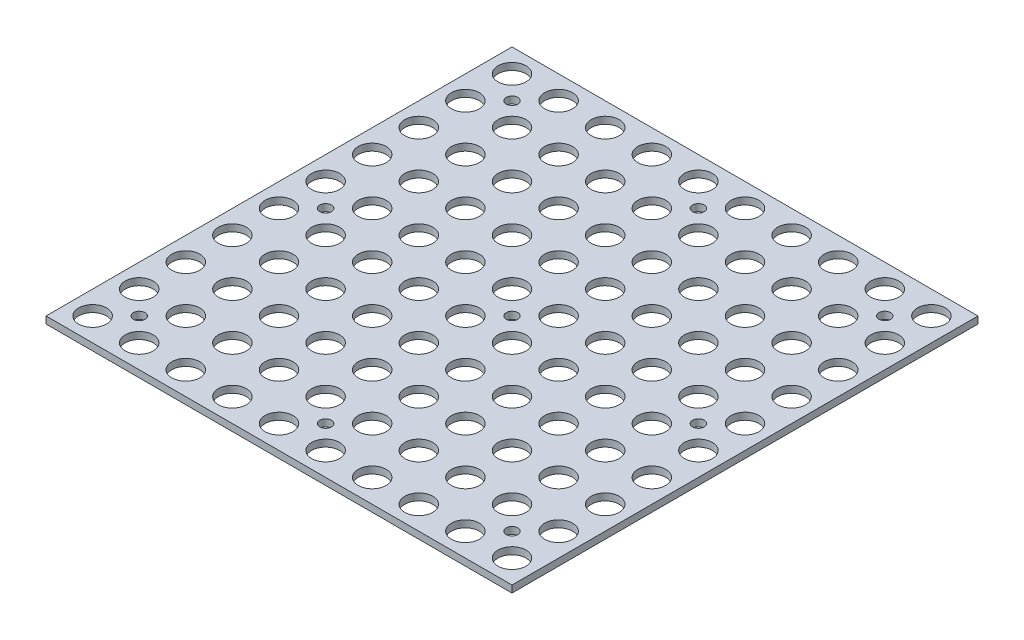
SolidWorks part; units mm, degrees
material "ABS"
ref_plane "Front Plane" through (0, 0, 0) normal (0, 0, 1) x (1, 0, 0)
ref_plane "Top Plane" through (0, 0, 0) normal (0, 1, 0) x (1, 0, 0)
ref_plane "Right Plane" through (0, 0, 0) normal (1, 0, 0) x (0, 0, -1)
sketch "Sketch1" plane through (0, 0, 0) normal (0, 1, 0) x (1, 0, 0)
  line L0 (-90, -90) -> (-70, -90) construction
  line L1 (-90, -90) -> (90, -90) construction
  line L2 (-90, -90) -> (-90, 90) construction
  line L3 (-90, 90) -> (90, 90) construction
  line L4 (90, -90) -> (90, 90) construction
  line L5 (-90, -90) -> (90, 90) construction
  line L6 (-90, 90) -> (90, -90) construction
  line L7 (-90, -90) -> (-90, -70) construction
  circle A0 centre (-90, -90) radius 6
  circle A1 centre (-70, -90) radius 6
  circle A2 centre (-50, -90) radius 6
  circle A3 centre (-30, -90) radius 6
  circle A4 centre (-10, -90) radius 6
  circle A5 centre (10, -90) radius 6
  circle A6 centre (30, -90) radius 6
  circle A7 centre (50, -90) radius 6
  circle A8 centre (70, -90) radius 6
  circle A9 centre (90, -90) radius 6
  circle A10 centre (-70, -70) radius 6
  circle A11 centre (-50, -70) radius 6
  circle A12 centre (-30, -70) radius 6
  circle A13 centre (-10, -70) radius 6
  circle A14 centre (10, -70) radius 6
  circle A15 centre (30, -70) radius 6
  circle A16 centre (50, -70) radius 6
  circle A17 centre (70, -70) radius 6
  circle A18 centre (90, -70) radius 6
  circle A19 centre (-70, -50) radius 6
  circle A20 centre (-50, -50) radius 6
  circle A21 centre (-30, -50) radius 6
  circle A22 centre (-10, -50) radius 6
  circle A23 centre (10, -50) radius 6
  circle A24 centre (30, -50) radius 6
  circle A25 centre (50, -50) radius 6
  circle A26 centre (70, -50) radius 6
  circle A27 centre (90, -50) radius 6
  circle A28 centre (-70, -30) radius 6
  circle A29 centre (-50, -30) radius 6
  circle A30 centre (-30, -30) radius 6
  circle A31 centre (-10, -30) radius 6
  circle A32 centre (10, -30) radius 6
  circle A33 centre (30, -30) radius 6
  circle A34 centre (50, -30) radius 6
  circle A35 centre (70, -30) radius 6
  circle A36 centre (90, -30) radius 6
  circle A37 centre (-70, -10) radius 6
  circle A38 centre (-50, -10) radius 6
  circle A39 centre (-30, -10) radius 6
  circle A40 centre (-10, -10) radius 6
  circle A41 centre (10, -10) radius 6
  circle A42 centre (30, -10) radius 6
  circle A43 centre (50, -10) radius 6
  circle A44 centre (70, -10) radius 6
  circle A45 centre (90, -10) radius 6
  circle A46 centre (-70, 10) radius 6
  circle A47 centre (-50, 10) radius 6
  circle A48 centre (-30, 10) radius 6
  circle A49 centre (-10, 10) radius 6
  circle A50 centre (10, 10) radius 6
  circle A51 centre (30, 10) radius 6
  circle A52 centre (50, 10) radius 6
  circle A53 centre (70, 10) radius 6
  circle A54 centre (90, 10) radius 6
  circle A55 centre (-70, 30) radius 6
  circle A56 centre (-50, 30) radius 6
  circle A57 centre (-30, 30) radius 6
  circle A58 centre (-10, 30) radius 6
  circle A59 centre (10, 30) radius 6
  circle A60 centre (30, 30) radius 6
  circle A61 centre (50, 30) radius 6
  circle A62 centre (70, 30) radius 6
  circle A63 centre (90, 30) radius 6
  circle A64 centre (-70, 50) radius 6
  circle A65 centre (-50, 50) radius 6
  circle A66 centre (-30, 50) radius 6
  circle A67 centre (-10, 50) radius 6
  circle A68 centre (10, 50) radius 6
  circle A69 centre (30, 50) radius 6
  circle A70 centre (50, 50) radius 6
  circle A71 centre (70, 50) radius 6
  circle A72 centre (90, 50) radius 6
  circle A73 centre (-70, 70) radius 6
  circle A74 centre (-50, 70) radius 6
  circle A75 centre (-30, 70) radius 6
  circle A76 centre (-10, 70) radius 6
  circle A77 centre (10, 70) radius 6
  circle A78 centre (30, 70) radius 6
  circle A79 centre (50, 70) radius 6
  circle A80 centre (70, 70) radius 6
  circle A81 centre (90, 70) radius 6
  circle A82 centre (-70, 90) radius 6
  circle A83 centre (-50, 90) radius 6
  circle A84 centre (-30, 90) radius 6
  circle A85 centre (-10, 90) radius 6
  circle A86 centre (10, 90) radius 6
  circle A87 centre (30, 90) radius 6
  circle A88 centre (50, 90) radius 6
  circle A89 centre (70, 90) radius 6
  circle A90 centre (90, 90) radius 6
  circle A91 centre (-90, -70) radius 6
  circle A92 centre (-90, -50) radius 6
  circle A93 centre (-90, -30) radius 6
  circle A94 centre (-90, -10) radius 6
  circle A95 centre (-90, 10) radius 6
  circle A96 centre (-90, 30) radius 6
  circle A97 centre (-90, 50) radius 6
  circle A98 centre (-90, 70) radius 6
  circle A99 centre (-90, 90) radius 6
  point P0 (0, 0)
  dimension "D3" = 12
  dimension "D2" = 180
  dimension "D6" = 20
  dimension "D7" = 20
  dimension "D4" = 10
  dimension "D5" = 10
sketch "Sketch3" plane through (0, 0, 0) normal (0, 1, 0) x (1, 0, 0)
  line L8 (-100, 100) -> (-100, -100)
  line L9 (-100, -100) -> (100, -100)
  line L10 (100, -100) -> (100, 100)
  line L11 (100, 100) -> (-100, 100)
  line L12 (-100, 100) -> (-100, -100)
  line L13 (-100, -100) -> (100, -100)
  line L14 (100, -100) -> (100, 100)
  line L15 (100, 100) -> (-100, 100)
  dimension "D1" = 10
extrude "Boss-Extrude2" add sketch "Sketch3" along normal blind 3
extrude "Cut-Extrude1" cut sketch "Sketch1" along normal through all
sketch "Sketch4" plane through (0, 3, 0) normal (0, 1, 0) x (1, 0, 0)
  line L0 (-100, -100) -> (100, -100) construction
  line L1 (-100, 100) -> (-100, -100) construction
  circle A0 centre (-80, -80) radius 2.5
  dimension "D1" = 5
  dimension "D2" = 20
  dimension "D3" = 20
extrude "Cut-Extrude2" cut sketch "Sketch4" against normal through all
pattern_linear "LPattern1" count 3 spacing 80 along (1, 0, 0) count 3 spacing 80 along (0, 0, -1) of "Cut-Extrude2"
